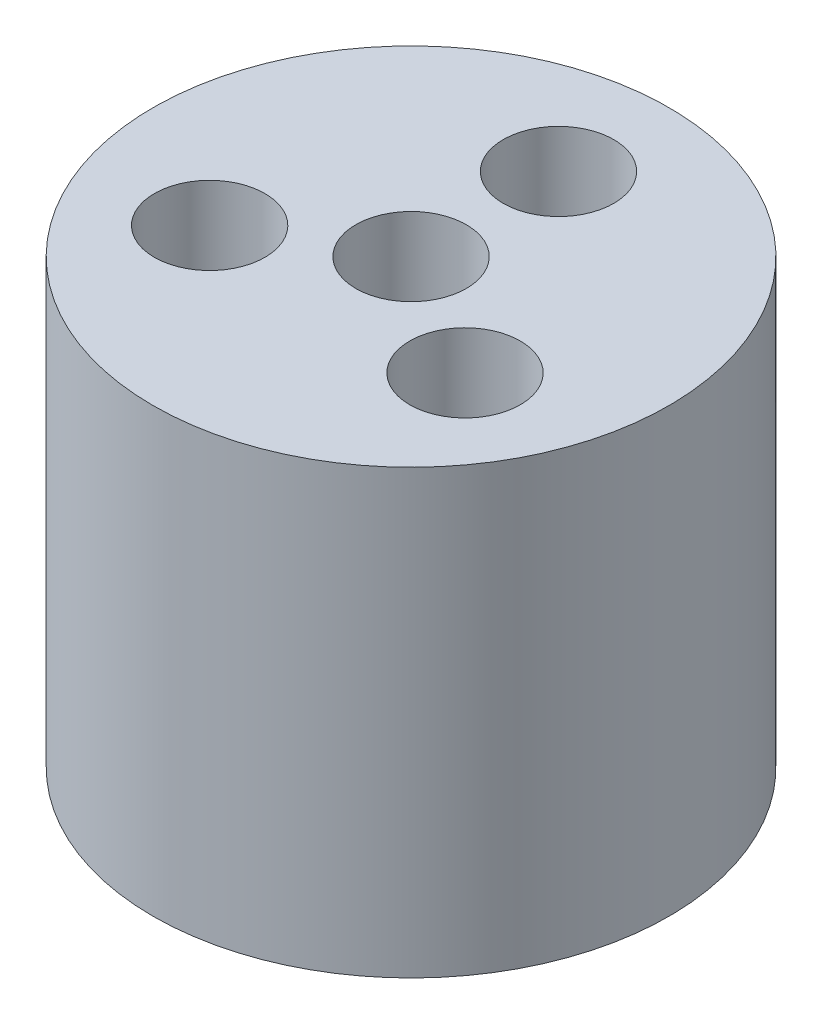
SolidWorks part; units mm, degrees
ref_plane "정면" through (0, 0, 0) normal (0, 0, 1) x (1, 0, 0)
ref_plane "윗면" through (0, 0, 0) normal (0, 1, 0) x (1, 0, 0)
ref_plane "우측면" through (0, 0, 0) normal (1, 0, 0) x (0, 0, -1)
sketch "스케치1" plane through (0, 0, 0) normal (0, 1, 0) x (1, 0, 0)
  circle A0 centre (0, 0) radius 14
  dimension "D1" = 28
extrude "보스-돌출1" add sketch "스케치1" along normal blind 24 contours A0
sketch "스케치2" plane through (0, 24, 0) normal (0, 1, 0) x (1, 0, 0)
  circle A0 centre (0, 0) radius 8 construction
  circle A1 centre (0, 0) radius 3
  circle A2 centre (0, 8) radius 3
  circle A3 centre (6.9282, -4) radius 3
  circle A4 centre (-6.9282, -4) radius 3
  point P12 (0, 0)
  dimension "D1" = 16
  dimension "D2" = 6
  dimension "D3" = 6
  dimension "D4" = 3
extrude "컷-돌출1" cut sketch "스케치2" against normal through all contours A2 | A4 | A1 | A3
